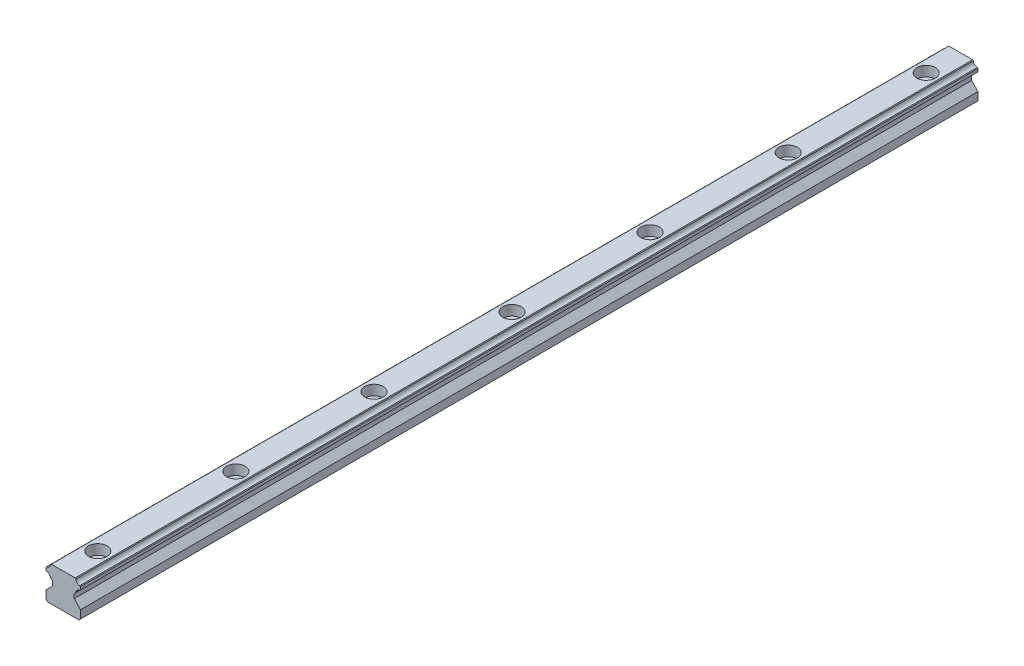
SolidWorks part; units mm, degrees
material "AISI 1045 Aço, trefilado"
ref_plane "Plano frontal" through (0, 0, 0) normal (0, 0, 1) x (1, 0, 0)
ref_plane "Plano superior" through (0, 0, 0) normal (0, 1, 0) x (1, 0, 0)
ref_plane "Plano direito" through (0, 0, 0) normal (1, 0, 0) x (0, 0, -1)
sketch "esboco-convertido" plane through (0, 0, 0) normal (0, 0, 1) x (1, 0, 0)
  line L0 (-5.17, 15) -> (-5.45, 14.72)
  line L1 (-7.15, 13.1117) -> (-7.43, 12.8317)
  line L2 (-7.43, 12.8317) -> (-7.43, 11.562)
  line L3 (-7.43, 11.562) -> (-7.15, 11.282)
  line L4 (-5.4472, 9.6452) -> (-4.73, 8.928)
  line L5 (-4.73, 8.928) -> (-4.73, 6.97)
  line L6 (-4.73, 6.97) -> (-7.5, 4.2)
  line L7 (-7.5, 4.2) -> (-7.5, 0.7)
  line L8 (-7.5, 0.7) -> (-6.8, 0)
  line L9 (-6.8, 0) -> (6.8, 0)
  line L19 (5.17, 15) -> (-5.17, 15)
  line L20 (0, 0) -> (0, 18.1934) construction
  line L21 (7.5, 0.7) -> (6.8, 0)
  line L22 (7.5, 4.2) -> (7.5, 0.7)
  line L23 (4.73, 6.97) -> (7.5, 4.2)
  line L24 (4.73, 8.928) -> (4.73, 6.97)
  line L25 (5.4472, 9.6452) -> (4.73, 8.928)
  line L26 (7.43, 11.562) -> (7.15, 11.282)
  line L27 (7.43, 12.8317) -> (7.43, 11.562)
  line L28 (7.15, 13.1117) -> (7.43, 12.8317)
  line L29 (5.17, 15) -> (5.45, 14.72)
  arc A0 (-7.15, 13.1117) -> (-5.45, 14.72) centre (-7.24, 14.9095) ccw
  arc A1 (-5.4472, 9.6452) -> (-7.15, 11.282) centre (-7.24, 9.4843) ccw
  arc A2 (5.4472, 9.6452) -> (7.15, 11.282) centre (7.24, 9.4843) cw
  arc A3 (7.15, 13.1117) -> (5.45, 14.72) centre (7.24, 14.9095) cw
  point P24 (0, 15)
  dimension "D9" = 1.8
  dimension "D10" = 1.8
  dimension "D20" = 7.24
  dimension "D1" = 15
  dimension "D2" = 15
  dimension "D3" = 4.2
  dimension "D4" = 45
  dimension "D5" = 0.7
  dimension "D6" = 6.8
  dimension "D7" = 2.77
  dimension "D8" = 1.958
  dimension "D11" = 4.73
  dimension "D12" = 5.17
  dimension "D13" = 0.7172
  dimension "D14" = 0.28
  dimension "D15" = 7.43
  dimension "D16" = 45
  dimension "D17" = 45
  dimension "D18" = 45
  dimension "D19" = 45
extrude "Boss-Extrude1" add sketch "esboco-convertido" along normal blind 390
hole_wizard "CBORE for M4 Hex Socket Head Cap Screw3" positions "Sketch8" profile "Sketch10" counterbore size "M4" standard "ISO" end condition through all
sketch "Sketch8" plane through (0, 15, 0) normal (0, 1, 0) x (1, 0, 0)
  line L0 (0, -390) -> (0, -375) construction
  line L1 (5.17, -390) -> (-5.17, -390) construction
  line L3 (0, 0) -> (0, -15) construction
  point P2 (0, -375)
  point P9 (0, -15)
  point P24 (0, -315)
  point P25 (0, -255)
  point P26 (0, -195)
  point P27 (0, -135)
  point P28 (0, -75)
  point P29 (0, -15)
  dimension "D1" = 15
  dimension "D2" = 15
  dimension "D3" = 7
sketch "Sketch10" plane through (0, 15, 15) normal (1, 0, 0) x (0, 0, 1)
  line L0 (0, 0) -> (0, 15)
  line L1 (0, 15) -> (2.25, 15)
  line L3 (2.25, 15) -> (2.25, 4.4)
  line L4 (2.25, 4.4) -> (4, 4.4)
  line L5 (4, 4.4) -> (4, 0)
  line L7 (4, 0) -> (0, 0)
  line L11 (0, -6.35) -> (0, 107.95) construction
  dimension "Thru Hole Dia." = 4.5
  dimension "Thru Hole Depth" = 15
  dimension "C'Bore Dia." = 8
  dimension "C'Bore Depth" = 4.4
